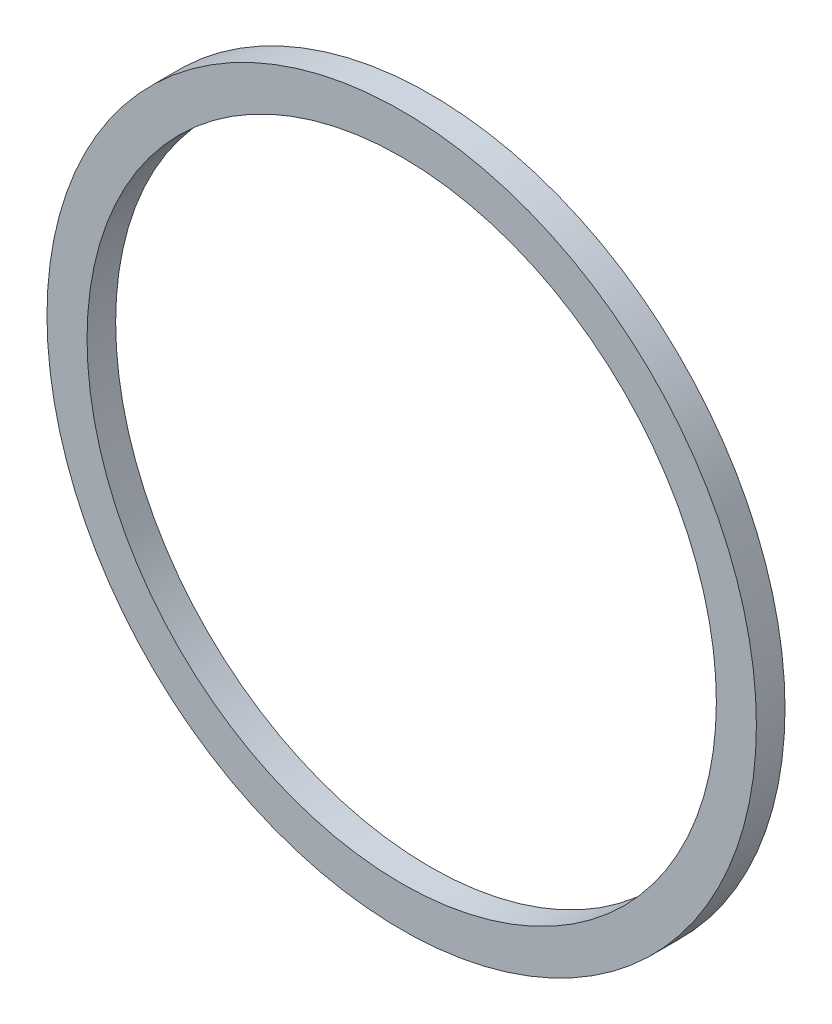
SolidWorks part; units mm, degrees
ref_plane "Plan1" through (0, 0, 0) normal (0, 0, 1) x (1, 0, 0)
ref_plane "Plan2" through (0, 0, 0) normal (0, 1, 0) x (1, 0, 0)
ref_plane "Plan3" through (0, 0, 0) normal (1, 0, 0) x (0, 0, -1)
sketch "Esquisse1" plane through (0, 0, 0) normal (0, 0, 1) x (1, 0, 0)
  circle A0 centre (0, 0) radius 27.5
  circle A1 centre (0, 0) radius 31
  dimension "D1" = 55
  dimension "D2" = 62
extrude "Base-Extrusion" add sketch "Esquisse1" along normal blind 2.5
